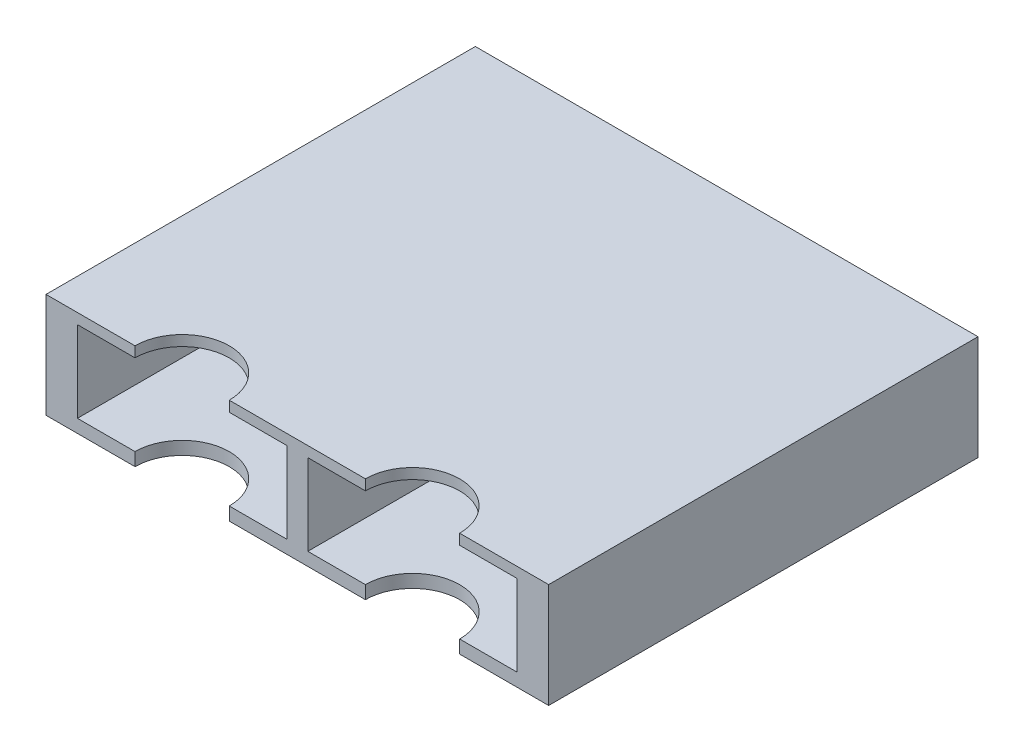
SolidWorks part; units mm, degrees
ref_plane "前视基准面" through (0, 0, 0) normal (0, 0, 1) x (1, 0, 0)
ref_plane "上视基准面" through (0, 0, 0) normal (0, 1, 0) x (1, 0, 0)
ref_plane "右视基准面" through (0, 0, 0) normal (1, 0, 0) x (0, 0, -1)
other "Configuration Table"
sketch "草图1" plane through (0, 0, 0) normal (0, 0, 1) x (1, 0, 0)
  line L1 (0, 0) -> (96, 0)
  line L2 (0, 0) -> (0, 20)
  line L3 (0, 20) -> (96, 20)
  line L4 (96, 0) -> (96, 20)
  dimension "D1" = 96
  dimension "D2" = 20
extrude "凸台-拉伸1" add sketch "草图1" along normal blind 82
sketch "草图2" plane through (0, 20, 0) normal (0, 1, 0) x (1, 0, 0)
  line L0 (48, 0) -> (48, -82) construction
  line L1 (96, 0) -> (0, 0) construction
  line L2 (96, -82) -> (0, -82) construction
  line L12 (46, 0) -> (46, -76.1956) construction
  line L13 (50, 0) -> (50, -76.1956) construction
  line L14 (0, -82) -> (0, 0) construction
  line L15 (17, -82) -> (35, -82)
  line L16 (79, -82) -> (61, -82)
  arc A8 (35, -82) -> (17, -82) centre (26, -82) ccw
  arc A9 (61, -82) -> (79, -82) centre (70, -82) cw
  dimension "D3" = 9
  dimension "D1" = 2
  dimension "D2" = 26
extrude "切除-拉伸2" cut sketch "草图2" against normal blind 20
sketch "草图3" plane through (0, 0, 82) normal (0, 0, 1) x (1, 0, 0)
  line L0 (46, 20) -> (46, 0) construction
  line L1 (96, 20) -> (79, 20) construction
  line L2 (0, 0) -> (17, 0) construction
  line L3 (50, 20) -> (50, 0) construction
  line L4 (87.5, 20) -> (87.5, 0) construction
  line L5 (46, 18) -> (6, 18)
  line L6 (46, 18) -> (46, 2.5)
  line L7 (46, 2.5) -> (6, 2.5)
  line L8 (6, 18) -> (6, 2.5)
  line L9 (129, 18) -> (129, 2.5)
  line L10 (169, 18) -> (169, 2.5)
  line L11 (129, 2.5) -> (169, 2.5)
  line L12 (129, 18) -> (169, 18)
  line L13 (48, 20) -> (48, 0) construction
  line L14 (61, 20) -> (35, 20) construction
  line L15 (35, 0) -> (61, 0) construction
  line L16 (50, 18) -> (50, 2.5)
  line L17 (50, 2.5) -> (90, 2.5)
  line L18 (50, 18) -> (90, 18)
  line L19 (90, 18) -> (90, 2.5)
  dimension "D1" = 15.5
  dimension "D2" = 2.5
  dimension "D3" = 40
extrude "切除-拉伸3" cut sketch "草图3" against normal blind 76
ref_plane "基准面1" through (48, 0, 0) normal (-1, 0, 0) x (0, 0, 1)
sketch "草图6" plane through (0, 0, 0) normal (0, -1, 0) x (1, 0, 0)
  line L1 (96, 82) -> (96, 0) construction
  line L2 (48, 8.525) -> (48, -8.525) construction
  line L3 (79, 82) -> (96, 82) construction
  line L4 (0, 0) -> (96, 0) construction
  circle A0 centre (86, 2.5) radius 1.5
  circle A1 centre (10, 2.5) radius 1.5
  circle A3 centre (93, 64) radius 1.5
  circle A4 centre (3, 64) radius 1.5
  point P22 (96, 28.4084)
  point P23 (96, 4.6184)
  dimension "D2" = 3
  dimension "D9" = 3
  dimension "D1" = 2.5
  dimension "D3" = 10
  dimension "D5" = 3
  dimension "D6" = 18
extrude "切除-拉伸5" cut sketch "草图6" against normal blind 10
